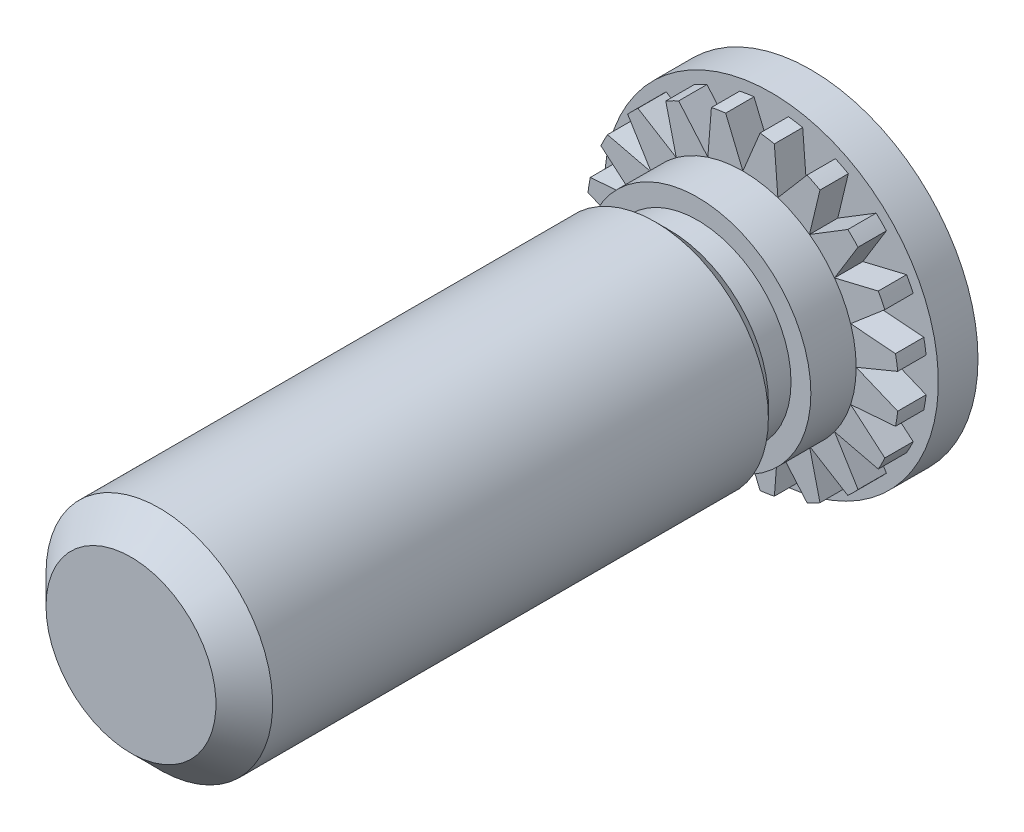
SolidWorks part; units mm, degrees
ref_plane "Спереди" through (0, 0, 0) normal (0, 0, 1) x (1, 0, 0)
ref_plane "Сверху" through (0, 0, 0) normal (0, 1, 0) x (1, 0, 0)
ref_plane "Справа" through (0, 0, 0) normal (1, 0, 0) x (0, 0, -1)
sketch "Эскиз1" plane through (0, 0, 0) normal (0, 0, 1) x (1, 0, 0)
  circle A0 centre (0, 0) radius 2.95
  dimension "D1" = 5.9
extrude "Вытянуть1" add sketch "Эскиз1" along normal blind 1.2
ref_axis "Ось1" through (0, 0, 14.8052) along (0, 0, -1)
sketch "Эскиз2" plane through (0, 0, 1.2) normal (0, 0, 1) x (1, 0, 0)
  circle A0 centre (0, 0) radius 2
  dimension "D1" = 4
extrude "Вытянуть2" add sketch "Эскиз2" along normal blind 1.9
sketch "Эскиз3" plane through (0, 0, 1.2) normal (0, 0, 1) x (1, 0, 0)
  line L0 (0, 0) -> (0, 2.95) construction
  line L1 (-0.3935, 2.95) -> (0.3935, 2.95)
  line L2 (0.3935, 2.95) -> (0, 2)
  line L3 (0, 2) -> (-0.3935, 2.95)
  circle A0 centre (0, 0) radius 2.95 construction
  circle A1 centre (0, 0) radius 2 construction
  dimension "D1" = 45
extrude "Вырез-Вытянуть1" cut sketch "Эскиз3" against normal blind 0.5
pattern_circular "Круговой массив1" count 20 over 360 about axis through (0, 0, 0) along (0, 0, 1) of "Вырез-Вытянуть1"
sketch "Эскиз4" plane through (0, 0, 0) normal (0, 1, 0) x (1, 0, 0)
  line L0 (0, -2.25) -> (2, -2.25) construction
  line L1 (0, -10.6426) -> (0, 0.6656) construction
  line L2 (-2, -3.1) -> (2, -3.1) construction
  line L3 (2, -2) -> (1.65, -2)
  line L4 (2, -2) -> (2, -2.5)
  line L5 (2, -2.5) -> (1.65, -2.5)
  line L6 (1.65, -2) -> (1.65, -2.5)
  dimension "D1" = 0.5
  dimension "D2" = 0.6
  dimension "D3" = 2
  dimension "D4" = 0.35
revolve "Вырез-Повернуть1" cut sketch "Эскиз4" angle 360 about axis through (0, 0, 14.8052) along (0, 0, -1)
sketch "Эскиз6" plane through (0, 0, 0) normal (1, 0, 0) x (0, 0, -1)
  line L0 (-3.1, 0) -> (-12, 0)
  line L1 (-3.1, 2) -> (-3.1, -2) construction
  line L2 (-10.6426, 0) -> (0.6656, 0) construction
  line L3 (-12, 0) -> (-12, -2)
  line L4 (-12, -2) -> (-3.1, -2)
  line L5 (-3.1, -2) -> (-3.1, 0)
  line L6 (0, -2.95) -> (0, 2.95) construction
  dimension "D1" = 12
  dimension "D2" = 2
revolve "Повернуть1" add sketch "Эскиз6" angle 360 about L0
chamfer "Фаска2" distance 0.5 angle 45 1 edges at (-2, 0, 12)
sketch "Эскиз7" plane through (0, 0, 1.2) normal (0, 0, 1) x (1, 0, 0)
  circle A0 centre (0, 0) radius 2.75
  circle A1 centre (0, 0) radius 2.95
  arc A2 (-1.4093, 2.5916) -> (-2.0293, 2.1412) centre (0, 0) ccw construction
  dimension "D1" = 0.2
extrude "Вырез-Вытянуть2" cut sketch "Эскиз7" against normal up to surface (0.5 mm away) up to face at (-2.4965, 0.8112, 0.7)
chamfer "Фаска3" distance 0.25 angle 45 1 edges at (2, 0, 2.5)
